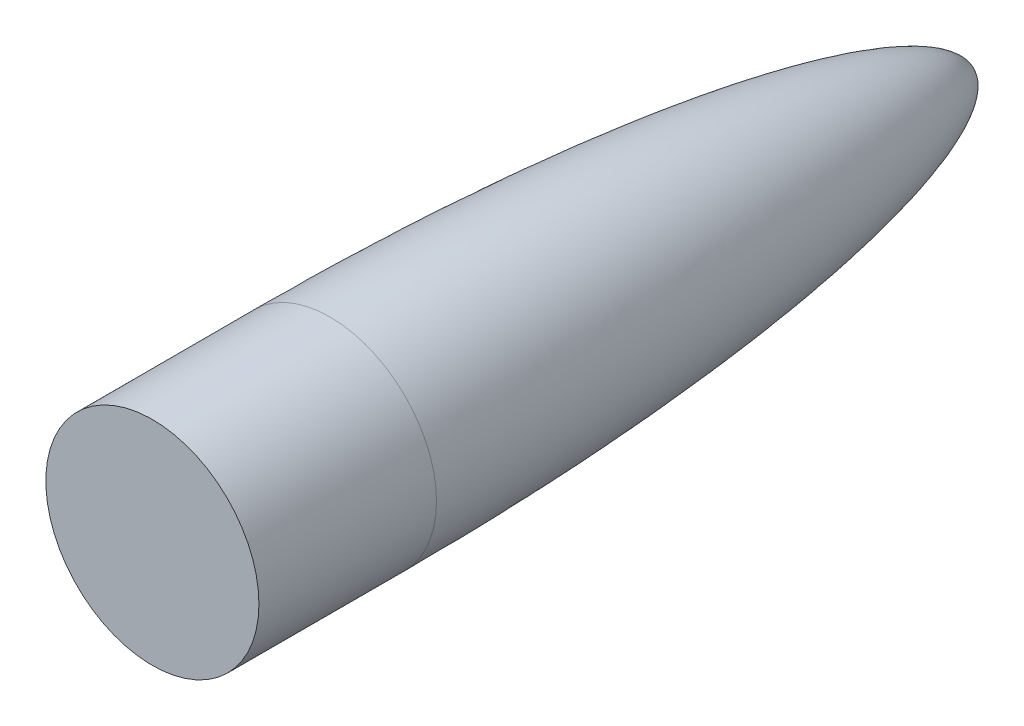
SolidWorks part; units mm, degrees
other "Markup1"
sketch "Sketch3" plane through (-76.2, 76.2, -762) normal (-0.6807, 0.6563, -0.3256) x (-0.115, 0.3432, 0.9322)
ref_plane "Front Plane" through (0, 0, 0) normal (0, 0, 1) x (1, 0, 0)
ref_plane "Top Plane" through (0, 0, 0) normal (0, 1, 0) x (1, 0, 0)
ref_plane "Right Plane"
sketch "Sketch1" plane through (0, 0, 0) normal (1, 0, 0) x (0, 0, -1)
  line L0 (0, 76.2) -> (0, 0)
  line L1 (0, 0) -> (457.2, 0)
  spline S0 degree 4 poles (-45.7212, 75.818) (-45.5436, 75.821) (-45.1859, 75.827) (-44.4536, 75.8388) (-43.0745, 75.8618) (-40.2991, 75.9034) (-36.5333, 75.9595) (-31.3026, 76.0222) (-24.5017, 76.0967) (-16.8071, 76.1514) (-10.4957, 76.1861) (-2.5895, 76.2003) (1.399, 76.2011) (6.722, 76.1936) (10.8243, 76.1797) (15.3251, 76.1589) (19.6131, 76.1311) (24.021, 76.0963) (28.3629, 76.0546) (33.8296, 75.9937) (40.3701, 75.9067) (50.1927, 75.7497) (63.2821, 75.4841) (78.555, 75.091) (93.8226, 74.5965) (106.9079, 74.0986) (117.8094, 73.6332) (126.5297, 73.2303) (137.4279, 72.6877) (150.5026, 71.9732) (165.7509, 71.0446) (183.1688, 69.8473) (200.5763, 68.5073) (217.9716, 67.0164) (235.3524, 65.3648) (252.7159, 63.5406) (270.0589, 61.5296) (287.3769, 59.3136) (308.9866, 56.2601) (334.842, 52.0843) (363.1481, 46.6366) (391.1648, 39.8262) (413.1662, 32.9594) (428.332, 26.8879) (437.961, 22.0574) (444.2769, 18.1347) (448.4811, 14.9275) (451.3625, 12.2396) (453.3709, 9.9391) (454.795, 7.9044) (455.8005, 6.0605) (456.4726, 4.413) (456.9556, 2.7152) (457.1501, 1.4237) (457.2, 0.5345) (457.2, 0) knots 0 0 0 0 0 0.001374 0.002747 0.005495 0.010989 0.021979 0.032968 0.043958 0.065937 0.076926 0.087916 0.096308 0.104701 0.113093 0.121486 0.129878 0.138271 0.146663 0.155056 0.171841 0.188626 0.222196 0.255767 0.289337 0.306122 0.322907 0.339692 0.356477 0.390047 0.423618 0.457188 0.490758 0.524328 0.557898 0.591469 0.625039 0.658609 0.692179 0.75932 0.82646 0.88025 0.91382 0.936432 0.951974 0.963004 0.970923 0.977039 0.982232 0.986451 0.989986 0.993161 0.995889 1 1 1 1 1 construction
  spline S1 degree 4 poles (0, 76.2) (0.9952, 76.2) (3.0164, 76.1988) (6.722, 76.1936) (10.8243, 76.1797) (15.3251, 76.1589) (19.6131, 76.1311) (24.021, 76.0963) (28.3629, 76.0546) (33.8296, 75.9937) (40.3701, 75.9067) (50.1927, 75.7497) (63.2821, 75.4841) (78.555, 75.091) (93.8226, 74.5965) (106.9079, 74.0986) (117.8094, 73.6332) (126.5297, 73.2303) (137.4279, 72.6877) (150.5026, 71.9732) (165.7509, 71.0446) (183.1688, 69.8473) (200.5763, 68.5073) (217.9716, 67.0164) (235.3524, 65.3648) (252.7159, 63.5406) (270.0589, 61.5296) (287.3769, 59.3136) (308.9866, 56.2601) (334.842, 52.0843) (363.1481, 46.6366) (391.1648, 39.8262) (413.1662, 32.9594) (428.332, 26.8879) (437.961, 22.0574) (444.2769, 18.1347) (448.4811, 14.9275) (451.3625, 12.2396) (453.3709, 9.9391) (454.795, 7.9044) (455.8005, 6.0605) (456.4726, 4.413) (456.9556, 2.7152) (457.1501, 1.4237) (457.2, 0.5345) (457.2, 0) knots 0.087916 0.087916 0.087916 0.087916 0.087916 0.096308 0.104701 0.113093 0.121486 0.129878 0.138271 0.146663 0.155056 0.171841 0.188626 0.222196 0.255767 0.289337 0.306122 0.322907 0.339692 0.356477 0.390047 0.423618 0.457188 0.490758 0.524328 0.557898 0.591469 0.625039 0.658609 0.692179 0.75932 0.82646 0.88025 0.91382 0.936432 0.951974 0.963004 0.970923 0.977039 0.982232 0.986451 0.989986 0.993161 0.995889 1 1 1 1 1
ref_axis "Axis1" through (0, 0, -480.06) along (0, 0, 1)
revolve "Revolve1" add sketch "Sketch1" angle 360 about axis through (0, 0, -480.06) along (0, 0, 1)
sketch "Sketch2" plane through (0, 0, 0) normal (0, 0, 1) x (1, 0, 0)
  circle A0 centre (0, 0) radius 76.2
  dimension "D1" = 152.4
extrude "Boss-Extrude1" add sketch "Sketch2" along normal blind 127
equation "\"BodyTubeRadius\"= 3in"
equation "\"ratio\"= 3"
equation "\"NoseConeLength\"= \"ratio\" * 2 * \"BodyTubeRadius\""
equation "\"D1@Sketch2\"=2*\"BodyTubeRadius\""
equation "\"BodyTubeLength\"=5"
